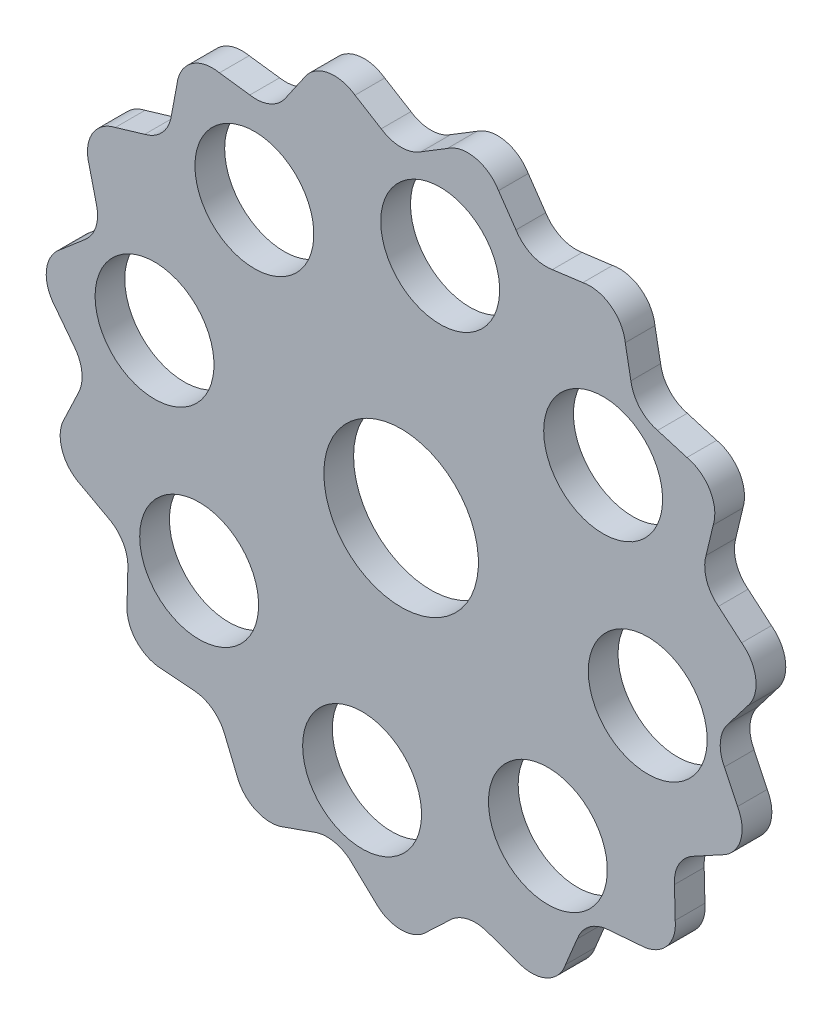
SolidWorks part; units mm, degrees
ref_plane "Plan de face" through (0, 0, 0) normal (0, 0, 1) x (1, 0, 0)
ref_plane "Plan de dessus" through (0, 0, 0) normal (0, 1, 0) x (1, 0, 0)
ref_plane "Plan de droite" through (0, 0, 0) normal (1, 0, 0) x (0, 0, -1)
sketch "Esquisse1" plane through (0, 0, 0) normal (0, 0, 1) x (1, 0, 0)
  line L0 (0, 0) -> (0, 70.8269) construction
  line L1 (0, 0) -> (-16.4135, 77.2197) construction
  line L2 (0, 0) -> (12.0589, 56.7326) construction
  line L3 (-3.3535, 55.0246) -> (3.3535, 55.0246) construction
  line L4 (0, 0) -> (-11.2473, 52.9146) construction
  line L5 (0, 0) -> (12.0589, 56.7326) construction
  line L6 (-11.2272, 52.82) -> (0, 0) construction
  line L7 (0, 0) -> (11.2272, 52.82) construction
  line L8 (-11.2272, 52.82) -> (11.2272, 52.82) construction
  line L9 (-7.7561, 57.7139) -> (7.7561, 57.7139) construction
  line L10 (-7.7561, 57.7139) -> (-3.3535, 55.0246)
  line L11 (3.3535, 55.0246) -> (7.7561, 57.7139)
  line L12 (0, 0) -> (17.0982, 80.4405) construction
  line L13 (16.3889, 55.879) -> (19.317, 51.6315)
  line L14 (25.4441, 48.9035) -> (30.5599, 49.5696)
  line L15 (37.7, 44.382) -> (38.6474, 39.3108)
  line L16 (43.1352, 34.3266) -> (48.0796, 32.8543)
  line L17 (52.4925, 25.211) -> (51.2953, 20.1929)
  line L18 (53.3678, 13.8142) -> (57.286, 10.4581)
  line L19 (58.2085, 1.6808) -> (55.0737, -2.4166)
  line L20 (54.3727, -9.0867) -> (56.5871, -13.7463)
  line L21 (53.8598, -22.14) -> (49.3295, -24.6081)
  line L22 (45.976, -30.4165) -> (46.1037, -35.5739)
  line L23 (40.1982, -42.1327) -> (35.0557, -42.5447)
  line L24 (29.6297, -46.487) -> (27.6486, -51.2505)
  line L25 (19.586, -54.8402) -> (14.7204, -53.125)
  line L26 (8.1601, -54.5194) -> (4.4128, -58.0653)
  line L27 (-4.4128, -58.0653) -> (-8.1601, -54.5194)
  line L28 (-14.7204, -53.125) -> (-19.586, -54.8402)
  line L29 (-27.6486, -51.2505) -> (-29.6297, -46.487)
  line L30 (-35.0557, -42.5447) -> (-40.1982, -42.1327)
  line L31 (-46.1037, -35.5739) -> (-45.976, -30.4165)
  line L32 (-49.3295, -24.6081) -> (-53.8598, -22.14)
  line L33 (-56.5871, -13.7463) -> (-54.3727, -9.0867)
  line L34 (-55.0737, -2.4166) -> (-58.2085, 1.6808)
  line L35 (-57.286, 10.4581) -> (-53.3678, 13.8142)
  line L36 (-51.2953, 20.1929) -> (-52.4925, 25.211)
  line L37 (-48.0796, 32.8543) -> (-43.1352, 34.3266)
  line L38 (-38.6474, 39.3108) -> (-37.7, 44.382)
  line L39 (-30.5599, 49.5696) -> (-25.4441, 48.9035)
  line L40 (-19.317, 51.6315) -> (-16.3889, 55.879)
  circle A4 centre (0, 0) radius 58 construction
  arc A5 (-3.3535, 55.0246) -> (3.3535, 55.0246) centre (0, 60) ccw
  arc A6 (12.4747, 58.6889) -> (7.7561, 57.7139) centre (11.2272, 52.82) ccw
  arc A8 (-12.4747, 58.6889) -> (-7.7561, 57.7139) centre (-11.2272, 52.82) cw
  arc A9 (12.4747, 58.6889) -> (16.3889, 55.879) centre (11.2272, 52.82) cw
  arc A10 (19.317, 51.6315) -> (25.4441, 48.9035) centre (24.4042, 54.8127) ccw
  arc A11 (35.2671, 48.541) -> (30.5599, 49.5696) centre (31.7404, 43.6869) ccw
  arc A12 (35.2671, 48.541) -> (37.7, 44.382) centre (31.7404, 43.6869) cw
  arc A13 (38.6474, 39.3108) -> (43.1352, 34.3266) centre (44.5887, 40.1478) ccw
  arc A14 (51.9615, 30) -> (48.0796, 32.8543) centre (46.7654, 27) ccw
  arc A15 (51.9615, 30) -> (52.4925, 25.211) centre (46.7654, 27) cw
  arc A16 (51.2953, 20.1929) -> (53.3678, 13.8142) centre (57.0634, 18.541) ccw
  arc A17 (59.6713, 6.2717) -> (57.286, 10.4581) centre (53.7042, 5.6445) ccw
  arc A18 (59.6713, 6.2717) -> (58.2085, 1.6808) centre (53.7042, 5.6445) cw
  arc A19 (55.0737, -2.4166) -> (54.3727, -9.0867) centre (59.6713, -6.2717) ccw
  arc A20 (57.0634, -18.541) -> (56.5871, -13.7463) centre (51.3571, -16.6869) ccw
  arc A21 (57.0634, -18.541) -> (53.8598, -22.14) centre (51.3571, -16.6869) cw
  arc A22 (49.3295, -24.6081) -> (45.976, -30.4165) centre (51.9615, -30) ccw
  arc A23 (44.5887, -40.1478) -> (46.1037, -35.5739) centre (40.1298, -36.1331) ccw
  arc A24 (44.5887, -40.1478) -> (40.1982, -42.1327) centre (40.1298, -36.1331) cw
  arc A25 (35.0557, -42.5447) -> (29.6297, -46.487) centre (35.2671, -48.541) ccw
  arc A26 (24.4042, -54.8127) -> (27.6486, -51.2505) centre (21.9638, -49.3315) ccw
  arc A27 (24.4042, -54.8127) -> (19.586, -54.8402) centre (21.9638, -49.3315) cw
  arc A28 (14.7204, -53.125) -> (8.1601, -54.5194) centre (12.4747, -58.6889) ccw
  arc A29 (0, -60) -> (4.4128, -58.0653) centre (0, -54) ccw
  arc A30 (0, -60) -> (-4.4128, -58.0653) centre (0, -54) cw
  arc A31 (-8.1601, -54.5194) -> (-14.7204, -53.125) centre (-12.4747, -58.6889) ccw
  arc A32 (-24.4042, -54.8127) -> (-19.586, -54.8402) centre (-21.9638, -49.3315) ccw
  arc A33 (-24.4042, -54.8127) -> (-27.6486, -51.2505) centre (-21.9638, -49.3315) cw
  arc A34 (-29.6297, -46.487) -> (-35.0557, -42.5447) centre (-35.2671, -48.541) ccw
  arc A35 (-44.5887, -40.1478) -> (-40.1982, -42.1327) centre (-40.1298, -36.1331) ccw
  arc A36 (-44.5887, -40.1478) -> (-46.1037, -35.5739) centre (-40.1298, -36.1331) cw
  arc A37 (-45.976, -30.4165) -> (-49.3295, -24.6081) centre (-51.9615, -30) ccw
  arc A38 (-57.0634, -18.541) -> (-53.8598, -22.14) centre (-51.3571, -16.6869) ccw
  arc A39 (-57.0634, -18.541) -> (-56.5871, -13.7463) centre (-51.3571, -16.6869) cw
  arc A40 (-54.3727, -9.0867) -> (-55.0737, -2.4166) centre (-59.6713, -6.2717) ccw
  arc A41 (-59.6713, 6.2717) -> (-58.2085, 1.6808) centre (-53.7042, 5.6445) ccw
  arc A42 (-59.6713, 6.2717) -> (-57.286, 10.4581) centre (-53.7042, 5.6445) cw
  arc A43 (-53.3678, 13.8142) -> (-51.2953, 20.1929) centre (-57.0634, 18.541) ccw
  arc A44 (-51.9615, 30) -> (-52.4925, 25.211) centre (-46.7654, 27) ccw
  arc A45 (-51.9615, 30) -> (-48.0796, 32.8543) centre (-46.7654, 27) cw
  arc A46 (-43.1352, 34.3266) -> (-38.6474, 39.3108) centre (-44.5887, 40.1478) ccw
  arc A47 (-35.2671, 48.541) -> (-37.7, 44.382) centre (-31.7404, 43.6869) ccw
  arc A48 (-35.2671, 48.541) -> (-30.5599, 49.5696) centre (-31.7404, 43.6869) cw
  arc A49 (-25.4441, 48.9035) -> (-19.317, 51.6315) centre (-24.4042, 54.8127) ccw
  arc A50 (-12.4747, 58.6889) -> (-16.3889, 55.879) centre (-11.2272, 52.82) ccw
  point P145 (0, 0)
  dimension "D2" = 6
  dimension "D3" = 24
  dimension "D5" = 6
  dimension "D7" = 60
  dimension "D8" = 54
  dimension "D11" = 15
  dimension "D14" = 116
  dimension "D4" = 6
  dimension "D6" = 12
  dimension "D10" = 12
  dimension "D9" = 12
extrude "Boss.-Extru.1" add sketch "Esquisse1" along normal blind 5
sketch "Esquisse2" plane through (0, 0, 0) normal (0, 0, -1) x (-1, 0, 0)
  line L0 (0, 0) -> (0, 51.5629) construction
  line L5 (0, 0) -> (27.1301, 37.3413) construction
  circle A0 centre (0, 0) radius 13
  circle A1 centre (24.687, 33.9787) radius 10
  circle A6 centre (41.4829, 6.5702) radius 10
  circle A7 centre (33.9787, -24.687) radius 10
  circle A8 centre (6.5702, -41.4829) radius 10
  circle A9 centre (-24.687, -33.9787) radius 10
  circle A10 centre (-41.4829, -6.5702) radius 10
  circle A11 centre (-33.9787, 24.687) radius 10
  circle A12 centre (-6.5702, 41.4829) radius 10
  point P23 (0, 0)
  dimension "D1" = 26
  dimension "D2" = 20
  dimension "D3" = 8
  dimension "D8" = 36
  dimension "D12" = 42
extrude "Enlèv. mat.-Extru.1" cut sketch "Esquisse2" against normal through all
ref_point "Point1"
